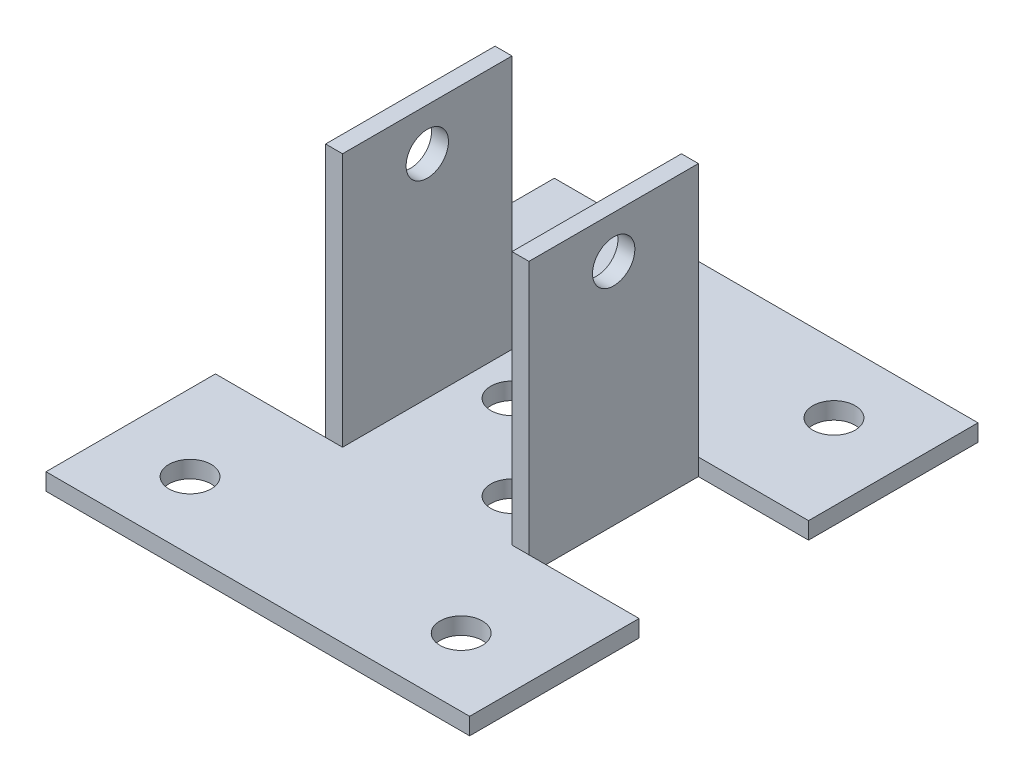
SolidWorks part; units mm, degrees
ref_plane "Plano frontal" through (0, 0, 0) normal (0, 0, 1) x (1, 0, 0)
ref_plane "Plano superior" through (0, 0, 0) normal (0, 1, 0) x (1, 0, 0)
ref_plane "Plano direito" through (0, 0, 0) normal (1, 0, 0) x (0, 0, -1)
sketch "Esboço1" plane through (0, 0, 0) normal (0, 1, 0) x (1, 0, 0)
  line L0 (10, 10) -> (10, -10)
  line L1 (10, -10) -> (25, -10)
  line L2 (25, -10) -> (25, -30)
  line L3 (25, -30) -> (-25, -30)
  line L4 (-25, -30) -> (-25, -10)
  line L5 (-25, -10) -> (-10, -10)
  line L6 (-10, -10) -> (-10, 10)
  line L8 (10, 10) -> (25, 10)
  line L9 (25, 10) -> (25, 30)
  line L10 (25, 30) -> (-25, 30)
  line L11 (-25, 30) -> (-25, 10)
  line L12 (-25, 10) -> (-10, 10)
  point P8 (0, 0)
  point P13 (0, 0)
  point P14 (0, 0)
  point P15 (0, 0)
  point P16 (0, 0)
  point P17 (0, 0)
  point P18 (0, 0)
  point P19 (0, 0)
  point P20 (0, 0)
  point P21 (0, 0)
  point P22 (0, 0)
  point P23 (0, 0)
  point P24 (0, 0)
extrude "Ressalto-extrusão1" add sketch "Esboço1" against normal blind 2
sketch "Esboço2" plane through (0, 0, 0) normal (0, 1, 0) x (1, 0, 0)
  line L0 (-12, 10) -> (-10, 10)
  line L1 (-10, 10) -> (-10, -10)
  line L2 (-10, -10) -> (-12, -10)
  line L3 (-12, -10) -> (-12, 10)
  line L4 (10, 10) -> (12, 10)
  line L5 (12, 10) -> (12, -10)
  line L6 (12, -10) -> (10, -10)
  line L7 (10, -10) -> (10, 10)
extrude "Ressalto-extrusão3" add sketch "Esboço2" along normal blind 30 and the other way blind 2
sketch "Esboço3" plane through (0, 0, 0) normal (0, 1, 0) x (1, 0, 0)
  circle A0 centre (16, -22) radius 2.5
  circle A1 centre (-16, -22) radius 2.5
  circle A2 centre (5, -5) radius 2.5
  circle A3 centre (-5, 5) radius 2.5
  circle A4 centre (16, 22) radius 2.5
  circle A5 centre (-16, 22) radius 2.5
  point P12 (0, 0)
  point P13 (0, 0)
  point P14 (0, 0)
  point P15 (0, 0)
  point P16 (0, 0)
  point P17 (0, 0)
  point P18 (0, 0)
  point P19 (0, 0)
  point P20 (0, 0)
  point P21 (0, 0)
  point P22 (0, 0)
  point P23 (0, 0)
  point P24 (0, 0)
extrude "Corte-extrusão1" cut sketch "Esboço3" against normal blind 2
sketch "Esboço4" plane through (0, 0, 0) normal (1, 0, 0) x (0, 0, -1)
  circle A0 centre (0, 25) radius 2.5
extrude "Corte-extrusão2" cut sketch "Esboço4" against normal through all both and the other way through all
